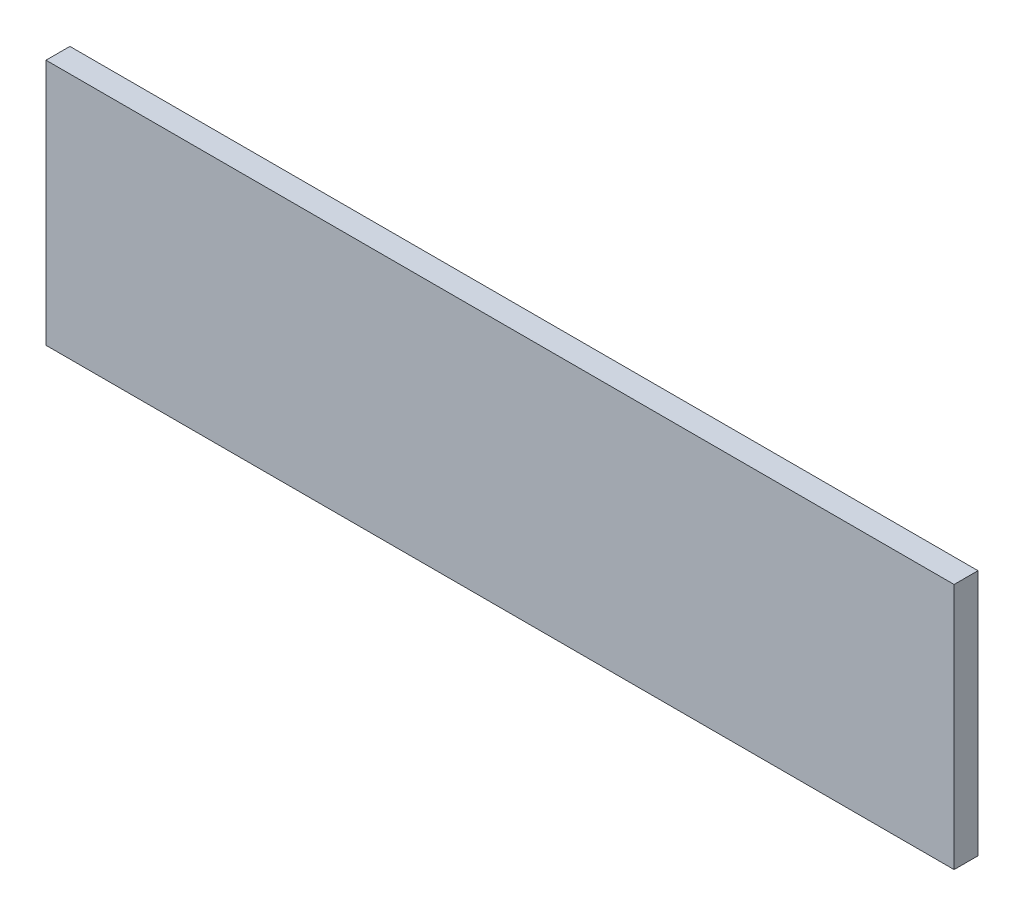
SolidWorks part; units mm, degrees
ref_plane "前视基准面" through (0, 0, 0) normal (0, 0, 1) x (1, 0, 0)
ref_plane "上视基准面" through (0, 0, 0) normal (0, 1, 0) x (1, 0, 0)
ref_plane "右视基准面" through (0, 0, 0) normal (1, 0, 0) x (0, 0, -1)
sketch "草图1" plane through (0, 0, 0) normal (0, 1, 0) x (1, 0, 0)
  line L1 (-57, 1.5) -> (57, 1.5)
  line L2 (-57, 1.5) -> (-57, -1.5)
  line L3 (-57, -1.5) -> (57, -1.5)
  line L4 (57, 1.5) -> (57, -1.5)
  line L5 (-57, 1.5) -> (57, -1.5) construction
  line L6 (-57, -1.5) -> (57, 1.5) construction
  point P0 (0, 0)
  dimension "D1" = 114
  dimension "D2" = 3
extrude "凸台-拉伸1" add sketch "草图1" along normal blind 31
